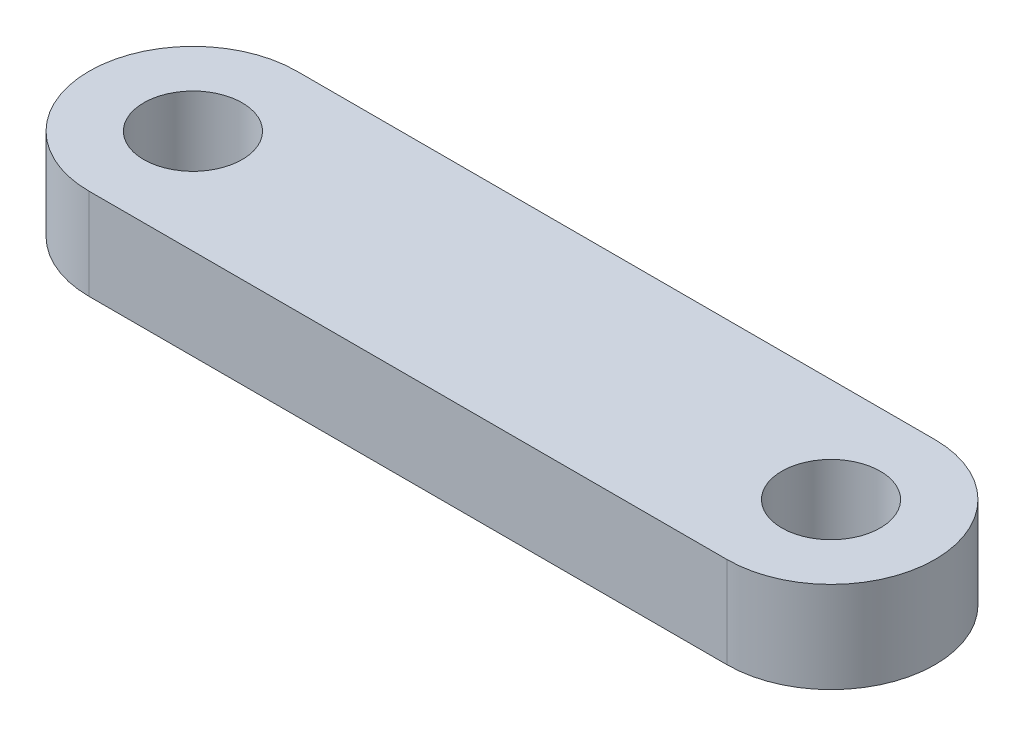
SolidWorks part; units mm, degrees
ref_plane "Front Plane" through (0, 0, 0) normal (0, 0, 1) x (1, 0, 0)
ref_plane "Top Plane" through (0, 0, 0) normal (0, 1, 0) x (1, 0, 0)
ref_plane "Right Plane" through (0, 0, 0) normal (1, 0, 0) x (0, 0, -1)
sketch "Sketch1" plane through (0, 0, 0) normal (0, 1, 0) x (1, 0, 0)
  line L2 (-32.32, 2.32) -> (2.68, 2.32)
  line L6 (-32.32, 8.02) -> (2.68, 8.02)
  line L7 (-32.32, -3.38) -> (2.68, -3.38)
  circle A0 centre (-32.32, 2.32) radius 2.7
  circle A1 centre (2.68, 2.32) radius 2.7
  arc A4 (2.68, -3.38) -> (2.68, 8.02) centre (2.68, 2.32) ccw
  circle A5 centre (-32.32, 2.32) radius 5.7
extrude "Boss-Extrude2" add sketch "Sketch1" along normal blind 5
